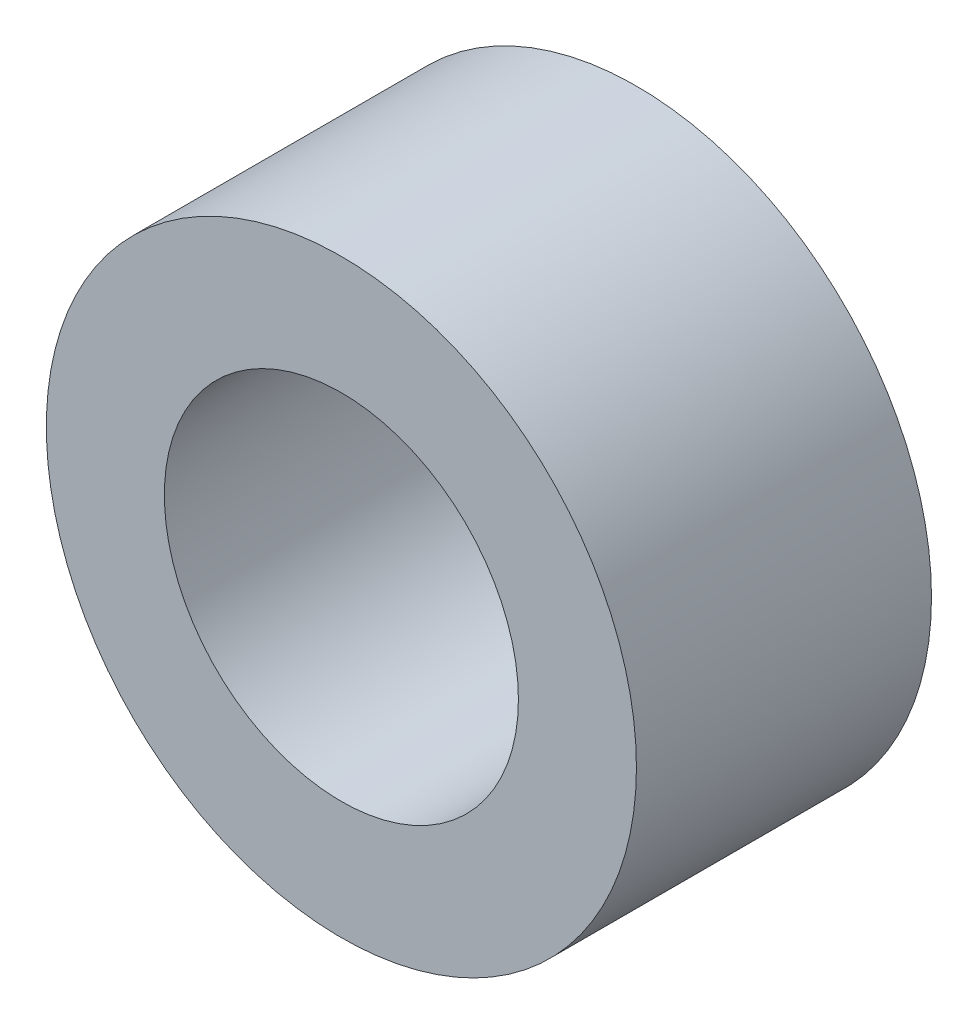
SolidWorks part; units mm, degrees
ref_plane "Front Plane" through (0, 0, 0) normal (0, 0, 1) x (1, 0, 0)
ref_plane "Top Plane" through (0, 0, 0) normal (0, 1, 0) x (1, 0, 0)
ref_plane "Right Plane" through (0, 0, 0) normal (1, 0, 0) x (0, 0, -1)
sketch "Sketch1" plane through (0, 0, 0) normal (0, 0, 1) x (1, 0, 0)
  circle A0 centre (0, 0) radius 3
  circle A1 centre (0, 0) radius 5
  dimension "D1" = 6
  dimension "D2" = 10
extrude "Boss-Extrude1" add sketch "Sketch1" along normal blind 5
